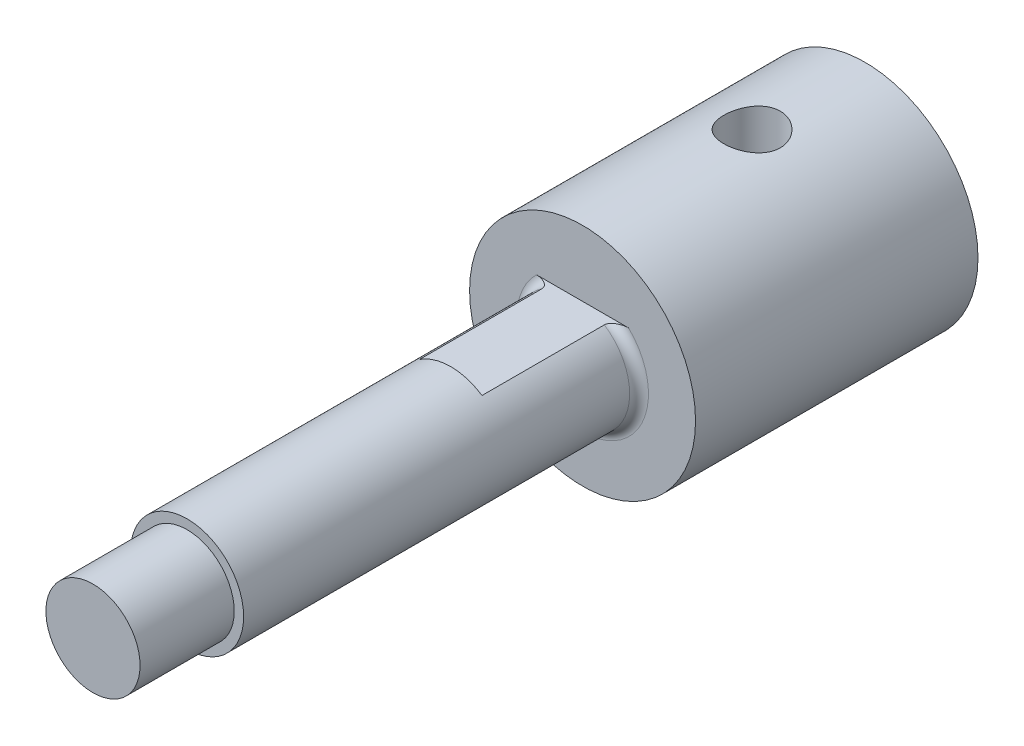
SolidWorks part; units mm, degrees
ref_plane "Front Plane" through (0, 0, 0) normal (0, 0, 1) x (1, 0, 0)
ref_plane "Top Plane" through (0, 0, 0) normal (0, 1, 0) x (1, 0, 0)
ref_plane "Right Plane" through (0, 0, 0) normal (1, 0, 0) x (0, 0, -1)
sketch "Sketch1" plane through (0, 0, 0) normal (0, 0, 1) x (1, 0, 0)
  circle A0 centre (0, 0) radius 6
  circle A3 centre (0, 0) radius 3
  dimension "D1" = 6
  dimension "D3" = 12
extrude "Boss-Extrude1" add sketch "Sketch1" along normal blind 11
sketch "Sketch2" plane through (0, 0, 0) normal (0, 1, 0) x (1, 0, 0)
  circle A0 centre (0, -6) radius 1.5
  dimension "D1" = 3
  dimension "D2" = 6
extrude "Cut-Extrude1" cut sketch "Sketch2" along normal through all
sketch "Sketch3" plane through (0, 0, 11) normal (0, 0, 1) x (1, 0, 0)
  circle A0 centre (0, 0) radius 6
  circle A1 centre (0, 0) radius 6 construction
extrude "Boss-Extrude2" add sketch "Sketch3" along normal blind 4
sketch "Sketch4" plane through (0, 0, 15) normal (0, 0, 1) x (1, 0, 0)
  line L0 (-1.6583, 2.5) -> (1.6583, 2.5)
  arc A1 (-1.6583, 2.5) -> (1.6583, 2.5) centre (0, 0) ccw
  point P5 (0, 2.5)
  dimension "D1" = 3
  dimension "D2" = 2.5
extrude "Boss-Extrude3" add sketch "Sketch4" along normal blind 7
sketch "Sketch5" plane through (0, 0, 22) normal (0, 0, 1) x (1, 0, 0)
  circle A0 centre (0, 0) radius 3
  arc A1 (-1.6583, 2.5) -> (1.6583, 2.5) centre (0, 0) ccw construction
extrude "Boss-Extrude6" add sketch "Sketch5" along normal blind 14
sketch "Sketch7" plane through (0, 0, 36) normal (0, 0, 1) x (1, 0, 0)
  circle A0 centre (0, 0) radius 2.5
  dimension "D1" = 5
extrude "Boss-Extrude7" add sketch "Sketch7" along normal blind 5
fillet "Fillet1" radius 0.5 1 edges at (0, -3, 15)
scale "Echelle1" scale about centroid uniform scaling yes scale factor 2
scale "Echelle2" scale about centroid uniform scaling yes scale factor 0.25
